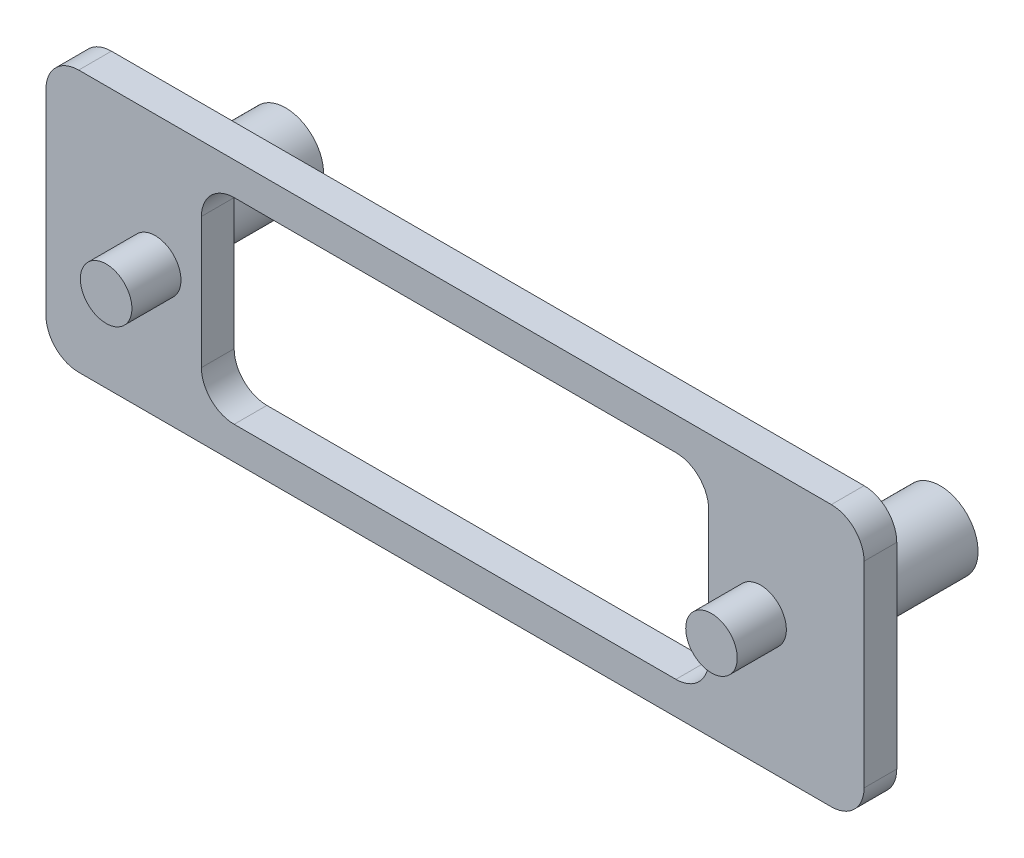
SolidWorks part; units mm, degrees
ref_plane "Front Plane" through (0, 0, 0) normal (0, 0, 1) x (1, 0, 0)
ref_plane "Top Plane" through (0, 0, 0) normal (0, 1, 0) x (1, 0, 0)
ref_plane "Right Plane" through (0, 0, 0) normal (1, 0, 0) x (0, 0, -1)
sketch "Sketch1" plane through (0, 0, 0) normal (0, 0, 1) x (1, 0, 0)
  line L1 (0, 0) -> (50, 0)
  line L2 (0, 0) -> (0, 16)
  line L3 (0, 16) -> (50, 16)
  line L4 (50, 0) -> (50, 16)
  dimension "D1" = 50
  dimension "D2" = 16
extrude "Boss-Extrude1" add sketch "Sketch1" along normal blind 2
sketch "Sketch2" plane through (0, 0, 2) normal (0, 0, 1) x (1, 0, 0)
  line L0 (6.675, 8) -> (43.675, 8) construction
  line L3 (0, 8) -> (5.1, 8) construction
  line L4 (0, 16) -> (0, 0) construction
  line L5 (45.25, 8) -> (50, 8) construction
  line L6 (50, 0) -> (50, 16) construction
  circle A0 centre (6.675, 8) radius 1.575
  circle A1 centre (43.675, 8) radius 1.575
  dimension "D2" = 3.15
  dimension "D3" = 3.15
  dimension "D1" = 37
  dimension "D4" = 4.75
  dimension "D5" = 5.1
extrude "Boss-Extrude2" add sketch "Sketch2" along normal blind 3
sketch "Sketch3" plane through (0, 0, 2) normal (0, 0, 1) x (1, 0, 0)
  line L0 (0, 5.0946) -> (9.5, 5.0946) construction
  line L1 (9.5, 2) -> (40.5, 2)
  line L2 (9.5, 2) -> (9.5, 14)
  line L3 (9.5, 14) -> (40.5, 14)
  line L4 (40.5, 2) -> (40.5, 14)
  line L5 (0, 16) -> (0, 0) construction
  line L6 (40.5, 5.6603) -> (50, 5.6603) construction
  line L7 (50, 0) -> (50, 16) construction
  line L8 (34.3076, 16) -> (34.3076, 14) construction
  line L9 (50, 16) -> (0, 16) construction
  line L10 (22.7374, 2) -> (22.7374, 0) construction
  line L11 (0, 0) -> (50, 0) construction
  dimension "D1" = 9.5
  dimension "D2" = 9.5
  dimension "D3" = 2
  dimension "D4" = 2
extrude "Cut-Extrude1" cut sketch "Sketch3" against normal blind 3
fillet "Fillet1" radius 2 4 edges at (40.5, 2, 1) (40.5, 14, 1) (9.5, 2, 1) (9.5, 14, 1)
fillet "Fillet2" radius 2 4 edges at (0, 0, 1) (0, 16, 1) (50, 0, 1) (50, 16, 1)
sketch "Sketch4" plane through (0, 0, 0) normal (0, 0, -1) x (-1, 0, 0)
  line L0 (-50, 8) -> (0, 8) construction
  line L1 (-50, 2) -> (-50, 14) construction
  line L2 (0, 14) -> (0, 2) construction
  circle A0 centre (-44.6436, 8) radius 2.325
  circle A5 centre (-4.6436, 8) radius 2.325
  circle A6 centre (-36.6436, 8) radius 2.325 [skipped]
  circle A7 centre (-28.6436, 8) radius 2.325 [skipped]
  circle A8 centre (-20.6436, 8) radius 2.325 [skipped]
  circle A9 centre (-12.6436, 8) radius 2.325 [skipped]
  dimension "D2" = 6
extrude "Boss-Extrude3" add sketch "Sketch4" along normal blind 8
